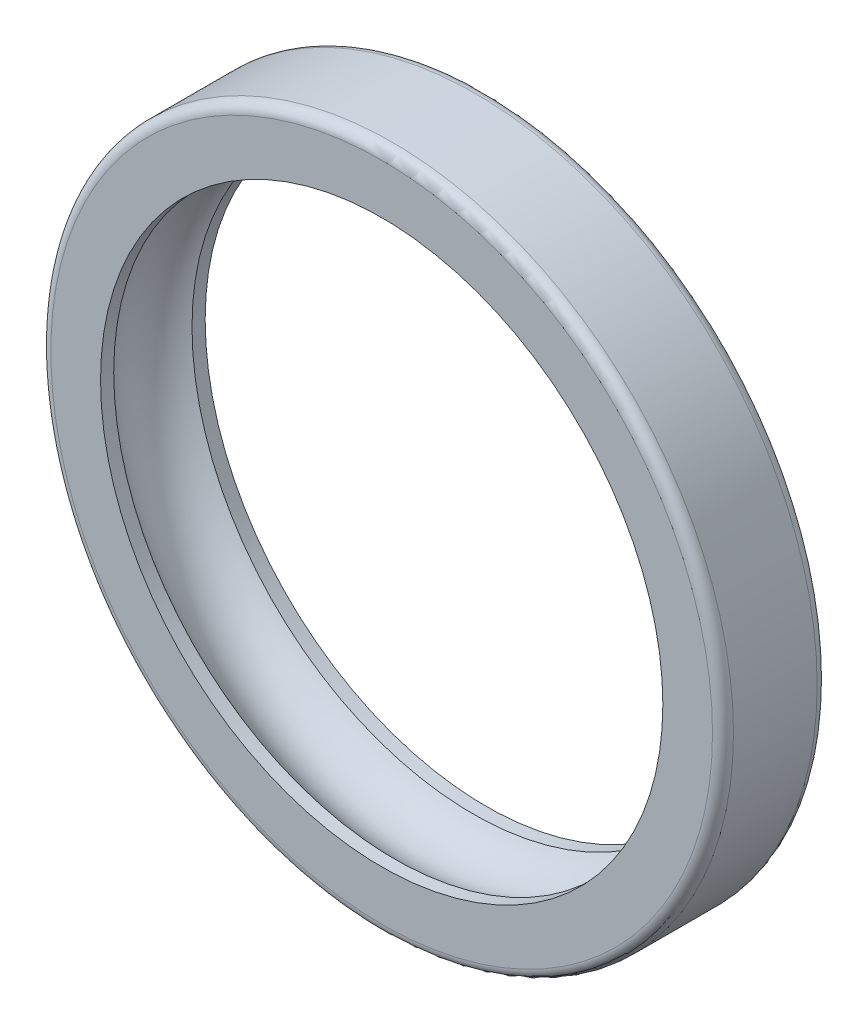
SolidWorks part; units mm, degrees
ref_plane "前视基准面" through (0, 0, 0) normal (0, 0, 1) x (1, 0, 0)
ref_plane "上视基准面" through (0, 0, 0) normal (0, 1, 0) x (1, 0, 0)
ref_plane "右视基准面" through (0, 0, 0) normal (1, 0, 0) x (0, 0, -1)
other "Configuration Table"
sketch "草图1" plane through (0, 0, 0) normal (0, 0, 1) x (1, 0, 0)
  circle A0 centre (0, 0) radius 65.25
  circle A1 centre (0, 0) radius 50.25
  dimension "D1" = 100.5
  dimension "D2" = 15
extrude "凸台-拉伸1" add sketch "草图1" along normal mid plane 20
sketch "草图2" plane through (0, 0, 0) normal (0, 1, 0) x (1, 0, 0)
  line L0 (0, 25.1963) -> (0, -28.6667) construction
  line L1 (53.75, 10) -> (53.75, 7.4833)
  line L2 (65.25, 10) -> (-65.25, 10) construction
  line L3 (-65.25, -10) -> (65.25, -10) construction
  line L4 (53.75, 10) -> (42.2937, 10)
  line L5 (42.2937, 10) -> (42.2937, -10)
  line L6 (42.2937, -10) -> (53.75, -10)
  line L7 (53.75, -7.4833) -> (53.75, -10)
  arc A0 (53.75, -7.4833) -> (53.75, 7.4833) centre (48.75, 0) ccw
  dimension "D1" = 18
  dimension "D2" = 48.75
  dimension "D3" = 5
revolve "切除-旋转2" cut sketch "草图2" angle 360 about L0
fillet "圆角1" radius 2 2 edges at (65.25, 0, -10) (65.25, 0, 10)
